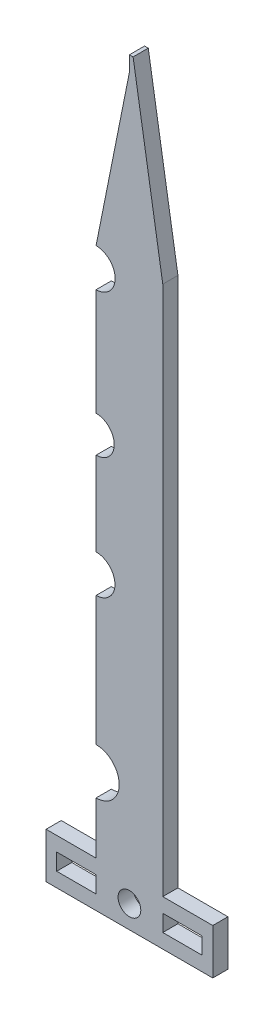
SolidWorks part; units mm, degrees
ref_plane "前视基准面" through (0, 0, 0) normal (0, 0, 1) x (1, 0, 0)
ref_plane "上视基准面" through (0, 0, 0) normal (0, 1, 0) x (1, 0, 0)
ref_plane "右视基准面" through (0, 0, 0) normal (1, 0, 0) x (0, 0, -1)
sketch "草图1" plane through (0, 0, 0) normal (0, 0, 1) x (1, 0, 0)
  line L0 (1.5, 0) -> (4.5, 0) construction
  line L1 (4.5, 0) -> (7, 0) construction
  line L2 (0, 0) -> (0, 100) construction
  line L3 (9.6, 1.1) -> (4.4, 1.1)
  line L4 (9.6, 1.1) -> (9.6, -1.1)
  line L5 (9.6, -1.1) -> (4.4, -1.1)
  line L6 (4.4, 1.1) -> (4.4, -1.1)
  line L7 (9.6, 1.1) -> (4.4, -1.1) construction
  line L8 (9.6, -1.1) -> (4.4, 1.1) construction
  line L9 (-9.6, -1.1) -> (-4.4, 1.1) construction
  line L10 (-9.6, 1.1) -> (-4.4, -1.1) construction
  line L11 (-4.5, 0) -> (-7, 0) construction
  line L12 (-4.4, 1.1) -> (-4.4, -1.1)
  line L13 (-9.6, -1.1) -> (-4.4, -1.1)
  line L14 (-9.6, 1.1) -> (-9.6, -1.1)
  line L15 (-9.6, 1.1) -> (-4.4, 1.1)
  line L16 (0, 0) -> (-11, 0) construction
  line L18 (-11, 0) -> (-11, -3)
  line L19 (-11, -3) -> (11, -3)
  line L20 (11, 0) -> (11, -3)
  line L22 (-11, 0) -> (-11, 3)
  line L23 (-11, 3) -> (-4.4, 3)
  line L24 (-4.4, 3) -> (-4.4, 73) construction
  line L26 (0.1608, 99.013) -> (4.4, 73) construction
  line L27 (4.4, 73) -> (4.4, 3)
  line L28 (4.4, 3) -> (11, 3)
  line L29 (11, 3) -> (11, 0)
  line L31 (-4.4, 3) -> (-4.4, 9.88)
  line L32 (-4.4, 15.9829) -> (-4.4, 33.026)
  line L33 (-4.4, 38) -> (-4.4, 49.0539)
  line L34 (-4.4, 53.8486) -> (-4.4, 67.9663)
  line L37 (0, 97.013) -> (0.4868, 97.013)
  line L38 (0.4868, 97.013) -> (4.4, 73)
  line L39 (0, 97.013) -> (0, 95.013)
  line L40 (0, 95.013) -> (-4.4, 73)
  circle A0 centre (0, 0) radius 1.5
  arc A1 (-4.4, 73) -> (-4.4, 67.9663) centre (-4.4, 70.4832) cw
  arc A2 (-4.4, 38) -> (-4.4, 33.026) centre (-4.4, 35.513) cw
  arc A3 (-4.4, 53.8486) -> (-4.4, 49.0539) centre (-4.4, 51.4512) cw
  arc A4 (-4.4, 15.9829) -> (-4.4, 9.88) centre (-4.4, 12.9314) cw
  point P21 (0, -3)
extrude "凸台-拉伸1" add sketch "草图1" along normal blind 2
